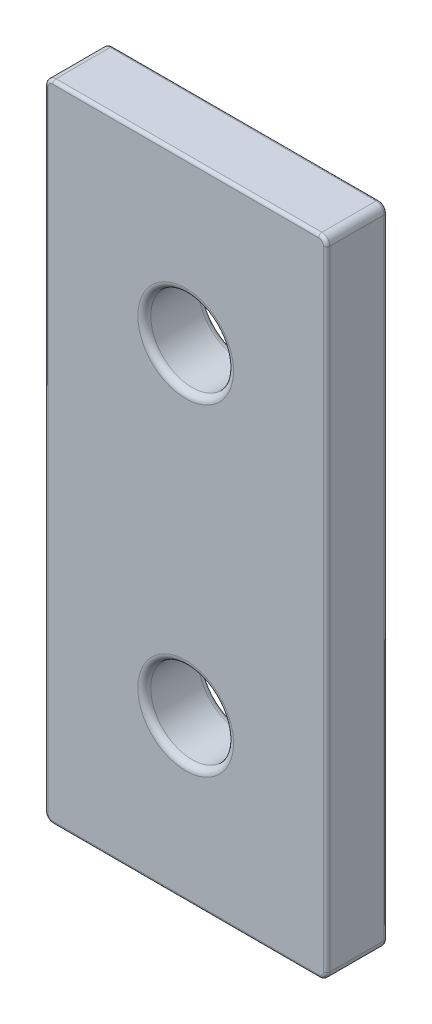
SolidWorks part; units mm, degrees
material "6061 Alloy"
ref_plane "Front Plane" through (0, 0, 0) normal (0, 0, 1) x (1, 0, 0)
ref_plane "Top Plane" through (0, 0, 0) normal (0, 1, 0) x (1, 0, 0)
ref_plane "Right Plane" through (0, 0, 0) normal (1, 0, 0) x (0, 0, -1)
sketch "Sketch1" plane through (0, 0, 0) normal (0, 0, 1) x (1, 0, 0)
  line L0 (-11.1125, 25.4) -> (-11.1125, -25.4)
  line L1 (-11.1125, 25.4) -> (11.1125, 25.4)
  line L2 (-11.1125, -25.4) -> (11.1125, -25.4)
  line L3 (11.1125, 25.4) -> (11.1125, -25.4)
  line L4 (-11.1125, 0) -> (11.1125, 0) construction
  line L5 (0, -12.7) -> (0, 12.7) construction
  line L6 (-3.175, 12.7) -> (-1.905, 12.7) construction
  circle A0 centre (0, 12.7) radius 3.2639
  circle A2 centre (0, 12.7) radius 3.175 construction
  circle A3 centre (25.4, 12.7) radius 3.2639
  circle A4 centre (25.4, -12.7) radius 3.2639
  circle A5 centre (0, -12.7) radius 3.2639
  dimension "Thru Hole Diameter" = 6.5278
  dimension "Mounting Fastener Thread Size" = 6.35
  dimension "Width" = 22.225
  dimension "Length" = 50.8
  dimension "Mounting Hole Vert CtoC" = 25.4
  dimension "Mounting Fastener Thread Pitch" = 1.27
  dimension "D1" = 12.7
  dimension "D2" = 11.1125
  dimension "Mounting Hole Horiz CtoC" = 25.4
  dimension "Mounting Hole Vertical Offset" = 12.7
  dimension "Mounting Hole Horizontal Offset" = 11.1125
  dimension "D50" = 2
  dimension "Number of Vertical Holes" = 2
sketch "Sketch2" plane through (0, 0, 0) normal (1, 0, 0) x (0, 0, -1)
  line L0 (-2.3876, 12.7) -> (2.3876, 12.7) construction
  line L1 (2.3876, 12.7) -> (15.0749, 12.7) construction
  dimension "Thickness" = 4.7752
  dimension "Mounting Fastener Thread Length" = 17.4625
sketch "Sketch3" plane through (0, 0, 0) normal (0, 0, 1) x (1, 0, 0)
  line L0 (-11.1125, 25.4) -> (-11.1125, -25.4) construction
  line L1 (-11.1125, -25.4) -> (11.1125, -25.4) construction
  line L2 (11.1125, 25.4) -> (11.1125, -25.4) construction
  line L3 (-11.1125, 25.4) -> (11.1125, 25.4) construction
  line L4 (-11.1125, 25.4) -> (-11.1125, -25.4)
  line L5 (-11.1125, -25.4) -> (11.1125, -25.4)
  line L6 (11.1125, 25.4) -> (11.1125, -25.4)
  line L7 (-11.1125, 25.4) -> (11.1125, 25.4)
extrude "Boss-Extrude1" add sketch "Sketch3" along normal up to vertex (2.3876 mm away) from vertex at -2.3876 starting at point (0, 12.7, -2.3876)
fillet "Fillet1" radius 0.635 4 edges at (11.1125, -25.4, 0) (-11.1125, -25.4, 0) (-11.1125, 25.4, 0) (11.1125, 25.4, 0)
sketch "Sketch4" plane through (0, 0, 2.3876) normal (0, 0, 1) x (1, 0, 0)
  circle A0 centre (0, 12.7) radius 3.2639 construction
  circle A1 centre (0, 12.7) radius 3.2639
extrude "Cut-Extrude1" cut sketch "Sketch4" against normal through all
pattern_linear "LPattern1" count 2 spacing 25.4 along (0, -1, 0) count 2 spacing 25.4 along (-1, 0, 0) of "Cut-Extrude1"
fillet "Fillet2" radius 0.254 16 edges at (10.9265, -25.214, -2.3876) (0, -25.4, -2.3876) (-10.9265, -25.214, -2.3876) (-11.1125, 0, -2.3876) (-10.9265, 25.214, -2.3876) (0, 25.4, -2.3876) (10.9265, 25.214, -2.3876) (10.9265, -25.214, 2.3876) (0, -25.4, 2.3876) (-10.9265, -25.214, 2.3876) (-11.1125, 0, 2.3876) (-10.9265, 25.214, 2.3876) (0, 25.4, 2.3876) (10.9265, 25.214, 2.3876) (11.1125, 0, -2.3876) (11.1125, 0, 2.3876)
fillet "Fillet3" radius 0.508 4 edges at (3.2639, 12.7, -2.3876) (3.2639, -12.7, -2.3876) (3.2639, 12.7, 2.3876) (3.2639, -12.7, 2.3876)
equation "\"D1@LPattern1\"=\"Number of Vertical Holes@Sketch1\""
equation "\"D4@LPattern1\"=\"D3@LPattern1\""
equation "\"D3@LPattern1\"=\"Mounting Hole Vert CtoC@Sketch1\""
equation "\"Mounting Hole Horiz CtoC@Sketch1\"=\"Mounting Hole Vert CtoC@Sketch1\""
